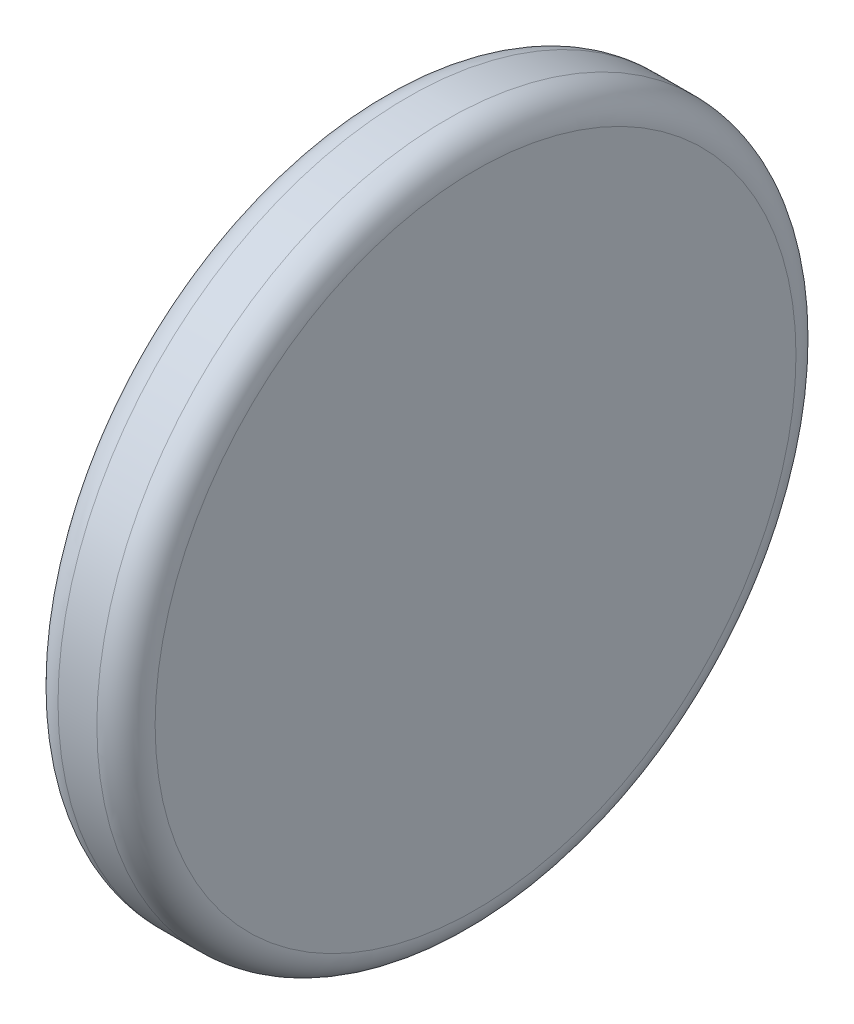
SolidWorks part; units mm, degrees
ref_plane "Front Plane" through (0, 0, 0) normal (0, 0, 1) x (1, 0, 0)
ref_plane "Top Plane" through (0, 0, 0) normal (0, 1, 0) x (1, 0, 0)
ref_plane "Right Plane" through (0, 0, 0) normal (1, 0, 0) x (0, 0, -1)
sketch "Sketch1" plane through (0, 0, 0) normal (0, 0, 1) x (1, 0, 0)
  line L1 (0, 0) -> (10, 0)
  line L2 (0, 0) -> (0, 36)
  line L3 (0, 36) -> (10, 36)
  line L4 (10, 0) -> (10, 36)
  dimension "D1" = 36
  dimension "D2" = 10
revolve "Revolve1" add sketch "Sketch1" angle 360 about L1
fillet "Fillet2" radius 3 2 edges at (10, 0, 36) (0, 0, 36)
